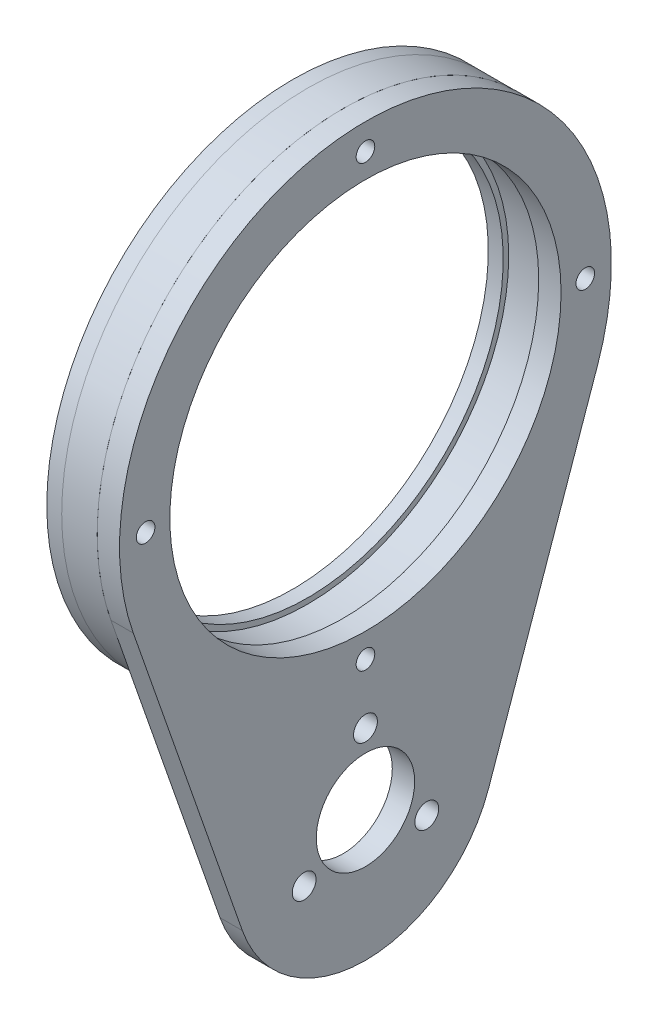
SolidWorks part; units mm, degrees
ref_plane "正面" through (0, 0, 0) normal (0, 0, 1) x (1, 0, 0)
ref_plane "平面" through (0, 0, 0) normal (0, 1, 0) x (1, 0, 0)
ref_plane "右側面" through (0, 0, 0) normal (1, 0, 0) x (0, 0, -1)
sketch "ｽｹｯﾁ2" plane through (0, 0, 0) normal (1, 0, 0) x (0, 0, -1)
  line L0 (0, 0) -> (0, 47) construction
  line L1 (-31.1538, 36.117) -> (-16.521, -5.7713)
  line L2 (31.1538, 36.117) -> (16.521, -5.7713)
  arc A0 (-16.521, -5.7713) -> (16.521, -5.7713) centre (0, 0) ccw
  arc A1 (31.1538, 36.117) -> (-31.1538, 36.117) centre (0, 47) ccw
  circle A2 centre (0, 0) radius 6.6
  circle A3 centre (0, 0) radius 9.5 construction
  circle A4 centre (0, 9.5) radius 1.6
  circle A5 centre (8.2272, -4.75) radius 1.6
  circle A6 centre (-8.2272, -4.75) radius 1.6
  circle A7 centre (0, 47) radius 26.25
  circle A8 centre (0, 47) radius 29.5 construction
  circle A9 centre (0, 76.5) radius 1.25
  circle A10 centre (0, 17.5) radius 1.25
  circle A11 centre (29.5, 47) radius 1.25
  circle A12 centre (-29.5, 47) radius 1.25
  point P17 (0, 0)
  dimension "D1" = 35
  dimension "D2" = 66
  dimension "D4" = 13.2
  dimension "D5" = 19
  dimension "D6" = 3.2
  dimension "D8" = 52.5
  dimension "D9" = 59
  dimension "D10" = 2.5
  dimension "D3" = 47
  dimension "D7" = 3
extrude "ﾎﾞｽ - 押し出し1" add sketch "ｽｹｯﾁ2" along normal blind 3
sketch "ｽｹｯﾁ6" plane through (0, 0, 0) normal (-1, 0, 0) x (0, 0, 1)
  circle A0 centre (0, 47) radius 33
  arc A2 (31.1538, 36.117) -> (-31.1538, 36.117) centre (0, 47) ccw construction
  circle A3 centre (0, 47) radius 26.9875
  circle A4 centre (0, 76.5) radius 1.6
  circle A5 centre (29.5, 47) radius 1.6
  circle A6 centre (0, 17.5) radius 1.6
  circle A7 centre (-29.5, 47) radius 1.6
  point P19 (0, 47)
  dimension "D1" = 53.975
  dimension "D2" = 3.2
  dimension "D3" = 4
extrude "ﾎﾞｽ - 押し出し4" add sketch "ｽｹｯﾁ6" along normal blind 4.763 separate body
sketch "ｽｹｯﾁ7" plane through (-4.763, 0, 0) normal (-1, 0, 0) x (0, 0, 1)
  circle A0 centre (0, 47) radius 33 construction
  circle A1 centre (0, 47) radius 33
  circle A2 centre (0, 47) radius 26.25 construction
  circle A3 centre (0, 47) radius 26.25
  circle A4 centre (0, 17.5) radius 1.6 construction
  circle A5 centre (29.5, 47) radius 1.6 construction
  circle A6 centre (-29.5, 47) radius 1.6 construction
  circle A7 centre (0, 76.5) radius 1.6 construction
  circle A8 centre (0, 17.5) radius 1.6
  circle A9 centre (29.5, 47) radius 1.6
  circle A10 centre (-29.5, 47) radius 1.6
  circle A11 centre (0, 76.5) radius 1.6
extrude "ﾎﾞｽ - 押し出し5" add sketch "ｽｹｯﾁ7" along normal blind 2 separate body
